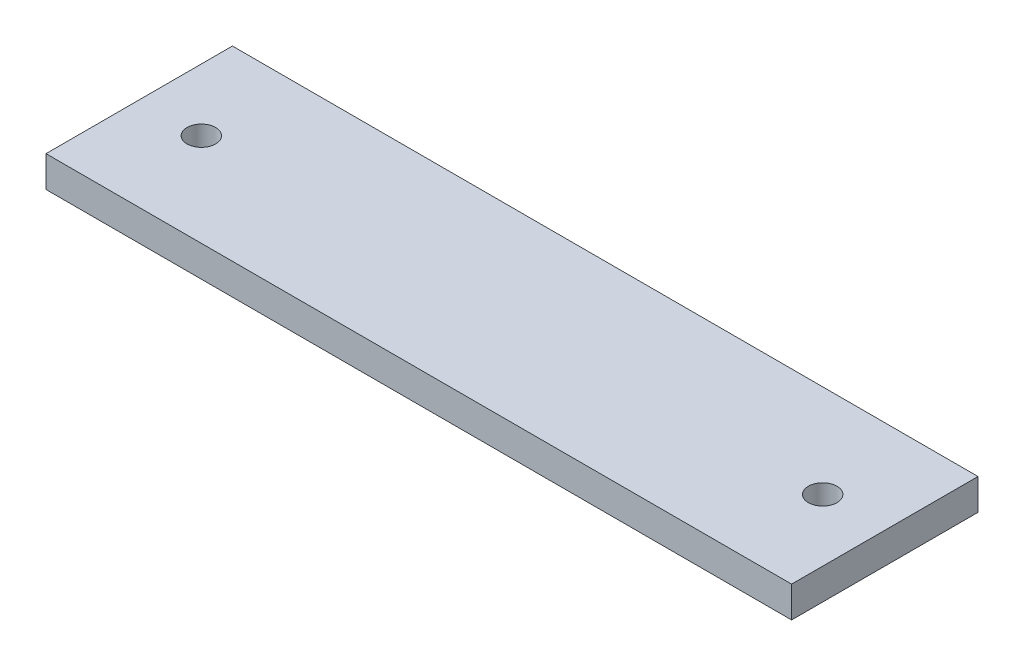
SolidWorks part; units mm, degrees
ref_plane "Front Plane" through (0, 0, 0) normal (0, 0, 1) x (1, 0, 0)
ref_plane "Top Plane" through (0, 0, 0) normal (0, 1, 0) x (1, 0, 0)
ref_plane "Right Plane" through (0, 0, 0) normal (1, 0, 0) x (0, 0, -1)
sketch "Sketch1" plane through (0, 0, 0) normal (0, 1, 0) x (1, 0, 0)
  line L1 (0, 0) -> (76.2, 0)
  line L2 (0, 0) -> (0, 19.05)
  line L3 (0, 19.05) -> (76.2, 19.05)
  line L4 (76.2, 0) -> (76.2, 19.05)
  circle A1 centre (6.35, 9.525) radius 1.4605
  circle A2 centre (69.85, 9.525) radius 1.4605
  point P11 (0, 0)
  point P12 (0, 0)
  point P13 (0, 0)
  point P14 (0, 0)
  point P15 (0, 0)
  dimension "D3" = 6.35
  dimension "D6" = 2.921
  dimension "D9" = 2.921
  dimension "D2" = 19.05
  dimension "D4" = 76.2
  dimension "D7" = 9.525
  dimension "D8" = 63.5
  dimension "D10" = 6.35
  dimension "D11" = 9.525
extrude "Boss-Extrude1" add sketch "Sketch1" along normal blind 3.175
